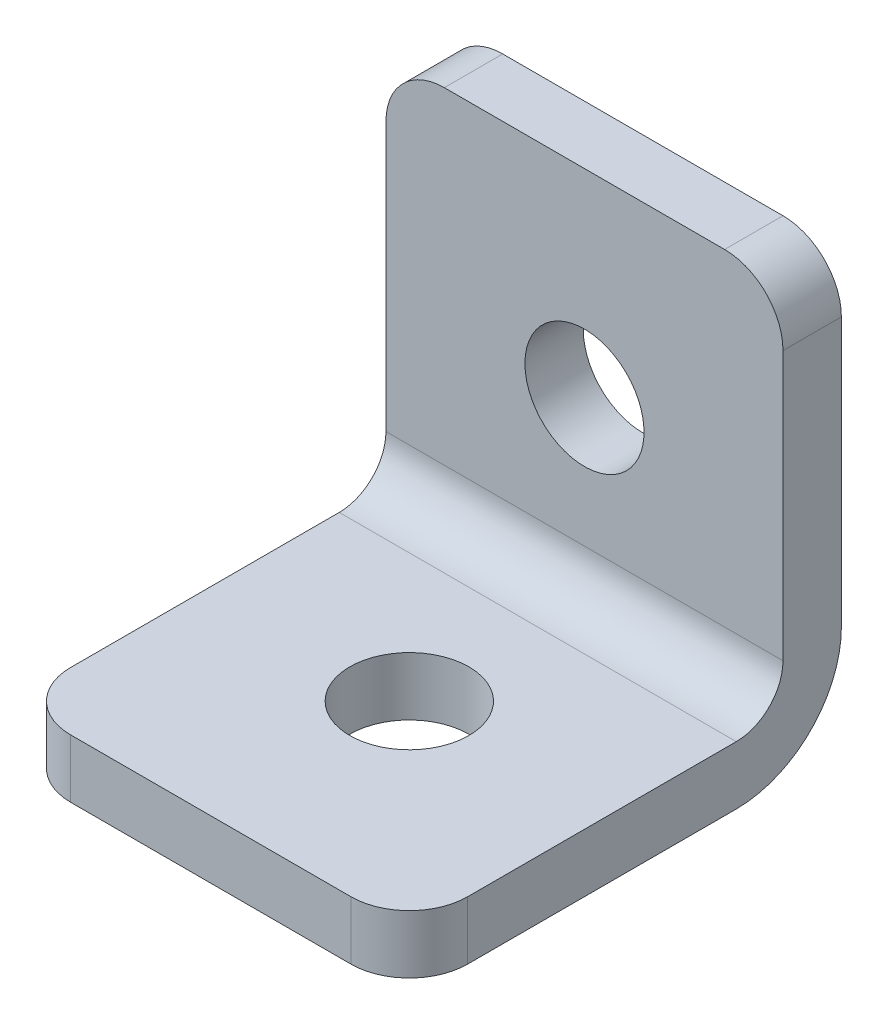
SolidWorks part; units mm, degrees
material "AISI 4340 Steel, normalized"
ref_plane "Спереди" through (0, 0, 0) normal (0, 0, 1) x (1, 0, 0)
ref_plane "Сверху" through (0, 0, 0) normal (0, 1, 0) x (1, 0, 0)
ref_plane "Справа" through (0, 0, 0) normal (1, 0, 0) x (0, 0, -1)
sketch "Эскиз1" plane through (0, 0, 0) normal (1, 0, 0) x (0, 0, -1)
  line L0 (14, 2.5) -> (0, 2.5)
  line L1 (0, 0) -> (0, 18.5) construction
  line L2 (18.5, 18.5) -> (18.5, 4.5)
  line L3 (14, 0) -> (0, 0)
  line L4 (18.5, 18.5) -> (0, 18.5) construction
  line L5 (0, 0) -> (0, 2.5)
  line L6 (16, 18.5) -> (18.5, 18.5)
  line L9 (16, 18.5) -> (16, 4.5)
  arc A0 (18.5, 4.5) -> (14, 0) centre (14, 4.5) cw
  arc A1 (16, 4.5) -> (14, 2.5) centre (14, 4.5) cw
  dimension "D3" = 4.5
  dimension "D5" = 2
  dimension "D1" = 18.5
  dimension "D2" = 18.5
  dimension "D4" = 2.5
  dimension "D6" = 2.5
extrude "Бобышка-Вытянуть1" add sketch "Эскиз1" along normal blind 17
fillet "Скругление1" radius 2.5 4 edges at (0, 18.5, -17.25) (17, 18.5, -17.25) (17, 1.25, 0) (0, 1.25, 0)
sketch "Эскиз2" plane through (0, 0, 0) normal (0, -1, 0) x (1, 0, 0)
  line L0 (8.5, 0) -> (8.5, -19.0977) construction
  line L1 (14.5, 0) -> (2.5, 0) construction
  line L2 (4.7982, -8.5) -> (12.8187, -8.5) construction
  line L3 (17, -18.5) -> (0, -18.5) construction
  circle A0 centre (8.5, -8.5) radius 2.55
  dimension "D2" = 5.1
  dimension "D1" = 10
extrude "Вырез-Вытянуть1" cut sketch "Эскиз2" against normal blind 17
sketch "Эскиз3" plane through (0, 0, -18.5) normal (0, 0, -1) x (-1, 0, 0)
  line L0 (-8.5, 19.3587) -> (-8.5, -0.7401) construction
  line L1 (-12.5814, 10) -> (-4.466, 10) construction
  line L2 (-17, 0) -> (0, 0) construction
  line L4 (-17, 4.5) -> (-17, 16) construction
  circle A0 centre (-8.5, 10) radius 2.55
  dimension "D3" = 5.1
  dimension "D1" = 10
  dimension "D2" = 8.5
extrude "Вырез-Вытянуть2" cut sketch "Эскиз3" against normal blind 17
